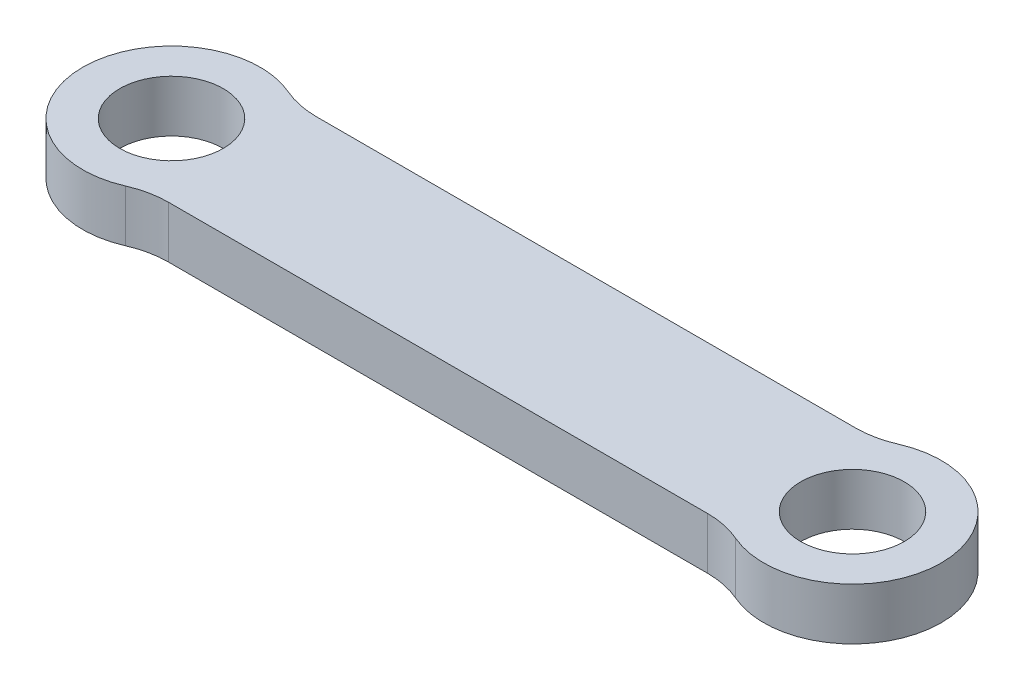
SolidWorks part; units mm, degrees
ref_plane "Front Plane" through (0, 0, 0) normal (0, 0, 1) x (1, 0, 0)
ref_plane "Top Plane" through (0, 0, 0) normal (0, 1, 0) x (1, 0, 0)
ref_plane "Right Plane" through (0, 0, 0) normal (1, 0, 0) x (0, 0, -1)
sketch "Sketch1" plane through (0, 0, 0) normal (0, 1, 0) x (1, 0, 0)
  line L0 (0, 0) -> (23, 0) construction
  line L1 (1.6583, 2.5) -> (21.3417, 2.5)
  line L2 (1.6583, -2.5) -> (21.3417, -2.5)
  circle A0 centre (0, 0) radius 3
  circle A1 centre (23, 0) radius 3
  circle A2 centre (0, 0) radius 1.75
  circle A3 centre (23, 0) radius 1.75
  dimension "D1" = 6
  dimension "D3" = 6
  dimension "D5" = 3.5
  dimension "D6" = 3.5
  dimension "D2" = 23
  dimension "D4" = 2.5
extrude "Boss-Extrude1" add sketch "Sketch1" along normal blind 1.75
fillet "Fillet1" radius 3 4 edges at (1.6583, 0.875, 2.5) (21.3417, 0.875, 2.5) (21.3417, 0.875, -2.5) (1.6583, 0.875, -2.5)
